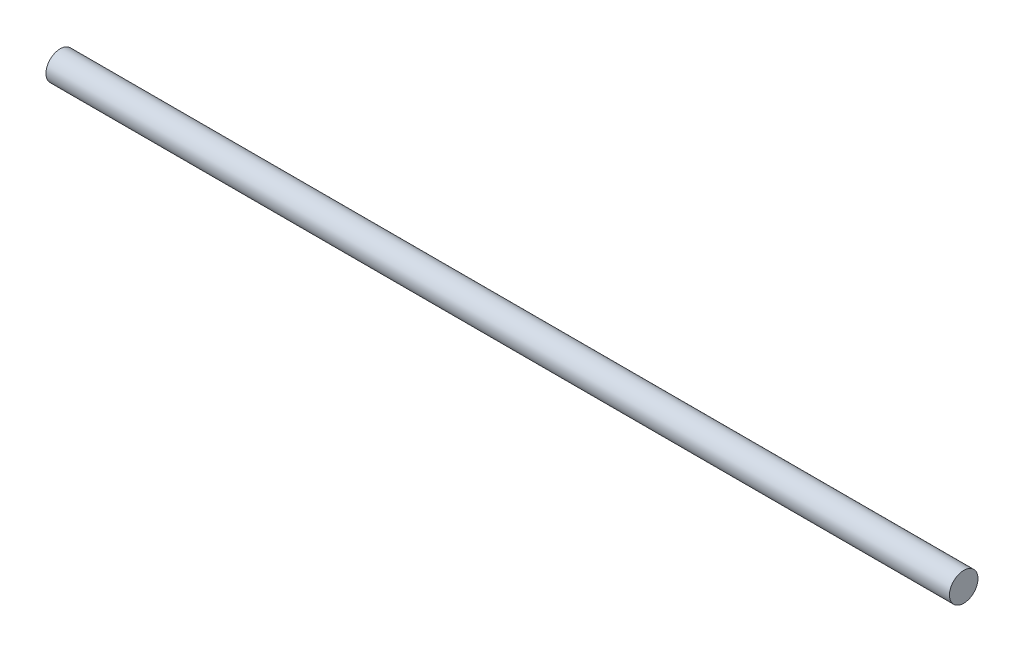
SolidWorks part; units mm, degrees
material "Stainless Steel (ferritic)"
ref_plane "Front Plane" through (0, 0, 0) normal (0, 0, 1) x (1, 0, 0)
ref_plane "Top Plane" through (0, 0, 0) normal (0, 1, 0) x (1, 0, 0)
ref_plane "Right Plane" through (0, 0, 0) normal (1, 0, 0) x (0, 0, -1)
sketch "Sketch1" plane through (0, 0, 0) normal (1, 0, 0) x (0, 0, -1)
  circle A0 centre (0, 0) radius 1.5
  dimension "D1" = 3
extrude "Boss-Extrude1" add sketch "Sketch1" along normal blind 95 contours A0
